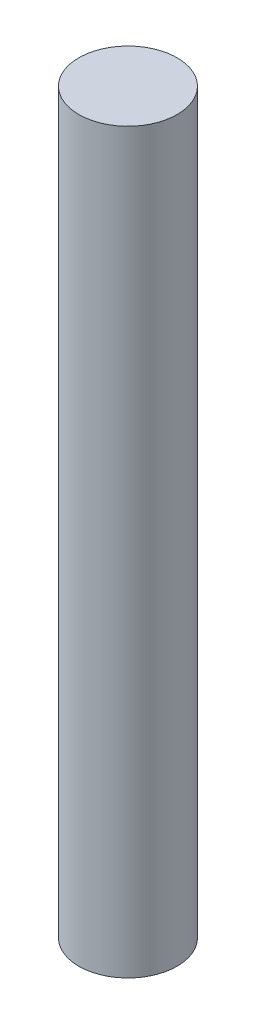
SolidWorks part; units mm, degrees
material "ASTM A36 Steel"
ref_plane "Front Plane" through (0, 0, 0) normal (0, 0, 1) x (1, 0, 0)
ref_plane "Top Plane" through (0, 0, 0) normal (0, 1, 0) x (1, 0, 0)
ref_plane "Right Plane" through (0, 0, 0) normal (1, 0, 0) x (0, 0, -1)
sketch "Sketch1" plane through (0, 0, 0) normal (0, 1, 0) x (1, 0, 0)
  circle A0 centre (0, 0) radius 8
  dimension "D1" = 16
extrude "Boss-Extrude1" add sketch "Sketch1" along normal mid plane 120
cosmetic thread "Cosmetic Thread1" parameters "D2"=13.797
